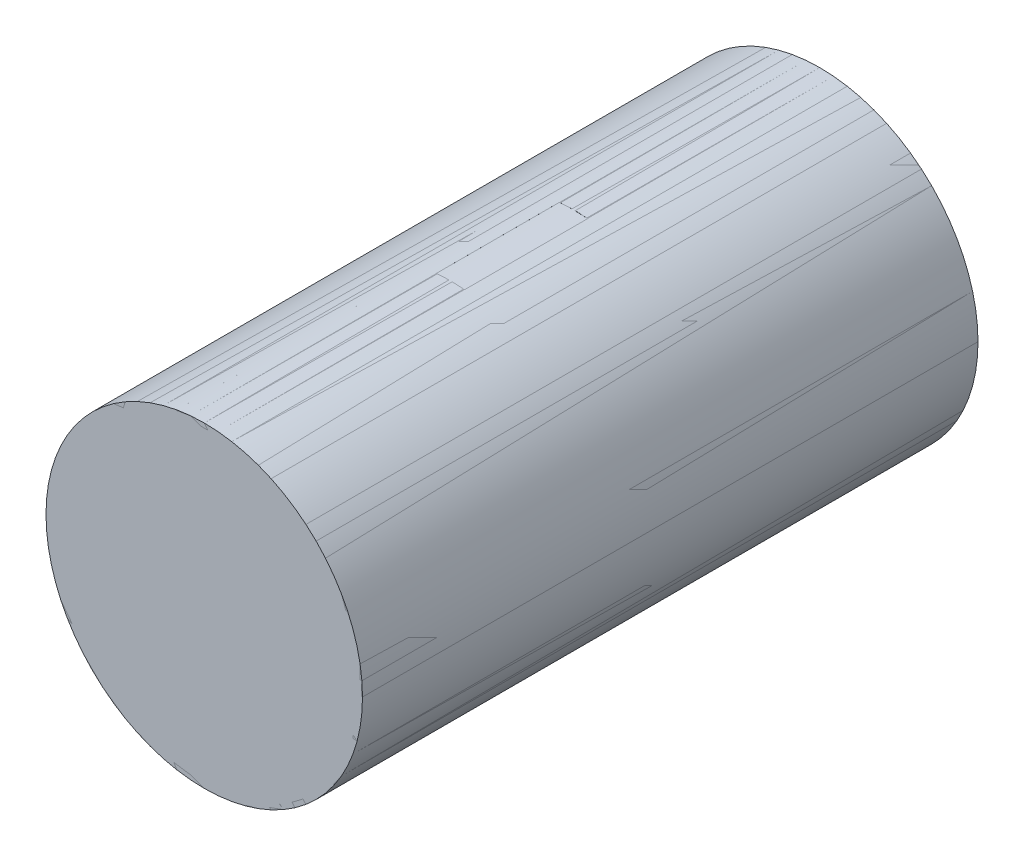
SolidWorks part; units mm, degrees
material "6061 Alloy"
ref_plane "Front Plane" through (0, 0, 0) normal (0, 0, 1) x (1, 0, 0)
ref_plane "Top Plane" through (0, 0, 0) normal (0, 1, 0) x (1, 0, 0)
ref_plane "Right Plane" through (0, 0, 0) normal (1, 0, 0) x (0, 0, -1)
sketch "Sketch2" plane through (0, 0, 0) normal (0, 0, 1) x (1, 0, 0)
  circle A0 centre (0, 0) radius 78.359
  circle A1 centre (0, 0) radius 76.2
  dimension "D1" = 156.718
  dimension "D2" = 152.4
extrude "Boss-Extrude1" add sketch "Sketch2" along normal blind 304.8
sketch "Sketch3" plane through (0, 0, 0) normal (0, 1, 0) x (1, 0, 0)
  line L0 (0, 0) -> (0, -152.4) construction
  line L2 (-6.9977, -182.88) -> (6.9977, -182.88)
  line L3 (-6.9977, -182.88) -> (-6.9977, -121.92)
  line L4 (-6.9977, -121.92) -> (6.9977, -121.92)
  line L5 (6.9977, -182.88) -> (6.9977, -121.92)
  line L6 (-6.9977, -182.88) -> (6.9977, -121.92) construction
  line L7 (-6.9977, -121.92) -> (6.9977, -182.88) construction
  dimension "D1" = 152.4
  dimension "D2" = 60.96
  dimension "D3" = 13.9954
extrude "Cut-Extrude1" cut sketch "Sketch3" along normal through all and the other way through all
sketch "Sketch4" plane through (0, 0, 304.8) normal (0, 0, 1) x (1, 0, 0)
  circle A1 centre (0, 0) radius 78.359
  circle A2 centre (0, 0) radius 78.359
  dimension "D1" = 0
extrude "Boss-Extrude2" add sketch "Sketch4" against normal through all separate body
